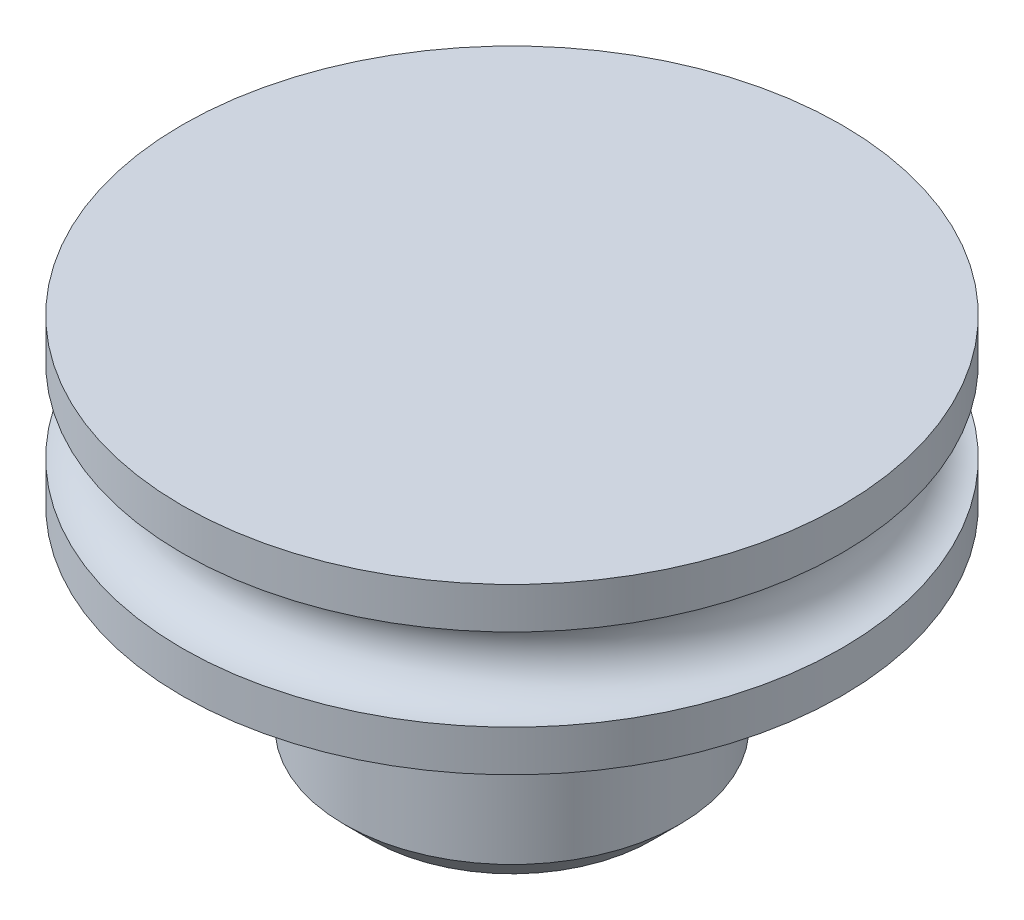
SolidWorks part; units mm, degrees
ref_plane "Front Plane" through (0, 0, 0) normal (0, 0, 1) x (1, 0, 0)
ref_plane "Top Plane" through (0, 0, 0) normal (0, 1, 0) x (1, 0, 0)
ref_plane "Right Plane" through (0, 0, 0) normal (1, 0, 0) x (0, 0, -1)
sketch "Sketch1" plane through (0, 0, 0) normal (0, 1, 0) x (1, 0, 0)
  circle A0 centre (0, 0) radius 3.05
  dimension "D1" = 6.1
extrude "Boss-Extrude1" add sketch "Sketch1" along normal blind 3
sketch "Sketch4" plane through (0, 3, 0) normal (0, 1, 0) x (1, 0, 0)
  circle A0 centre (0, 0) radius 3.6
  dimension "D1" = 7.2
extrude "Boss-Extrude3" add sketch "Sketch4" along normal blind 1
sketch "Sketch2" plane through (0, 4, 0) normal (0, 1, 0) x (1, 0, 0)
  circle A0 centre (0, 0) radius 6
  dimension "D1" = 12
extrude "Boss-Extrude2" add sketch "Sketch2" along normal blind 3
ref_axis "Axis1" through (0, 9.1152, 0) along (0, -1, 0)
sketch "Sketch3" plane through (0, 0, 0) normal (0, 0, 1) x (1, 0, 0)
  line L0 (-6, 7) -> (-6, 4) construction
  circle A0 centre (-6, 5.5) radius 0.75
  dimension "D1" = 1.5
revolve "Cut-Revolve1" cut sketch "Sketch3" angle 360 about axis through (0, 9.1152, 0) along (0, -1, 0)
chamfer "Chamfer1" distance 0.5 angle 45 1 edges at (0, 0, 3.05)
